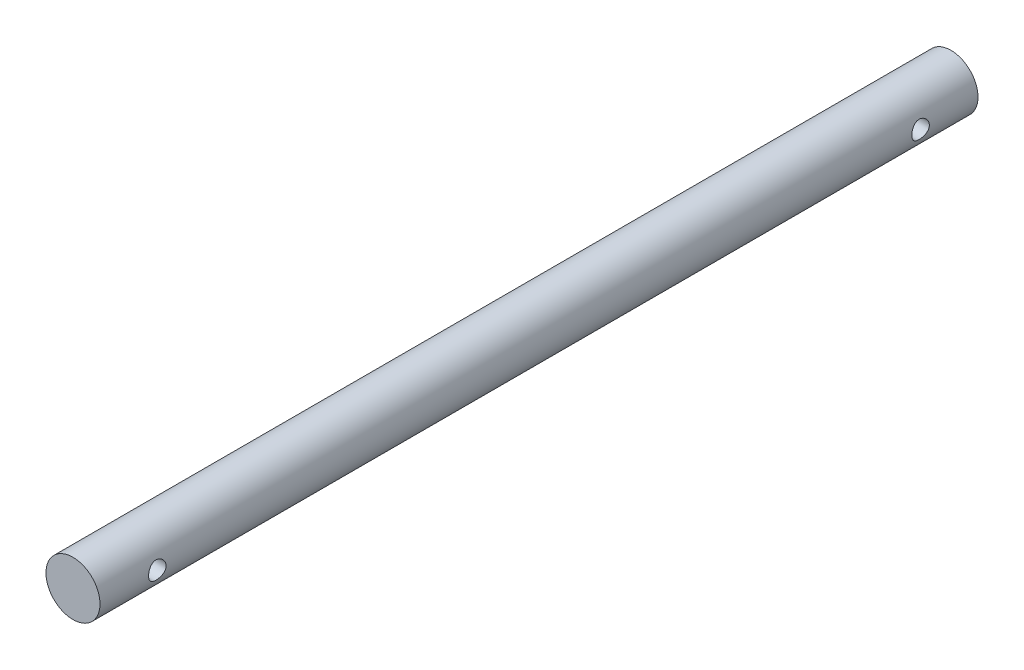
SolidWorks part; units mm, degrees
ref_plane "Front Plane" through (0, 0, 0) normal (0, 0, 1) x (1, 0, 0)
ref_plane "Top Plane" through (0, 0, 0) normal (0, 1, 0) x (1, 0, 0)
ref_plane "Right Plane" through (0, 0, 0) normal (1, 0, 0) x (0, 0, -1)
sketch "Sketch1" plane through (0, 0, 0) normal (0, 0, 1) x (1, 0, 0)
  circle A0 centre (0, 0) radius 4
  dimension "D1" = 8
extrude "Boss-Extrude1" add sketch "Sketch1" along normal mid plane 130
sketch "Sketch2" plane through (0, 0, 0) normal (1, 0, 0) x (0, 0, -1)
  line L0 (65, -4) -> (65, 4) construction
  circle A0 centre (56.5, 0) radius 1.3
  dimension "D1" = 2.6
  dimension "D2" = 8.5
extrude "Cut-Extrude1" cut sketch "Sketch2" against normal through all both and the other way through all
mirror "Mirror1" about plane through (0, 0, 0) normal (0, 0, 1) of "Cut-Extrude1"
